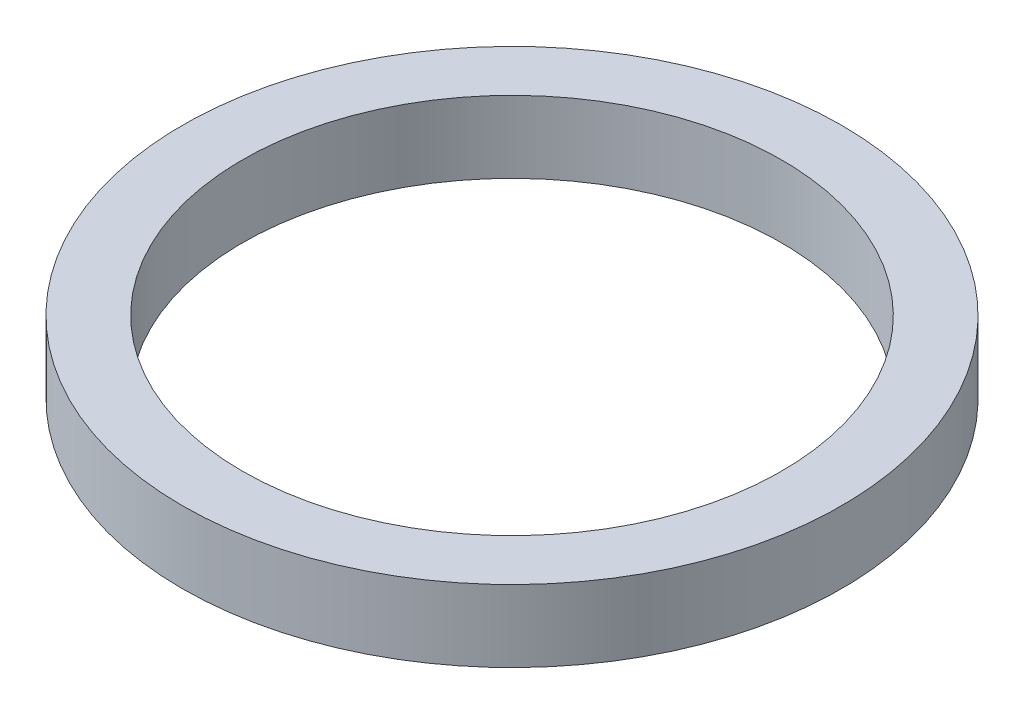
SolidWorks part; units mm, degrees
ref_plane "前基準面" through (0, 0, 0) normal (0, 0, 1) x (1, 0, 0)
ref_plane "上基準面" through (0, 0, 0) normal (0, 1, 0) x (1, 0, 0)
ref_plane "右基準面" through (0, 0, 0) normal (1, 0, 0) x (0, 0, -1)
sketch "草圖1" plane through (0, 0, 0) normal (0, 1, 0) x (1, 0, 0)
  circle A0 centre (0, 0) radius 27.5
  circle A1 centre (0, 0) radius 22.5
  dimension "D1" = 45
  dimension "D2" = 55
extrude "填料-伸長1" add sketch "草圖1" along normal mid plane 6
